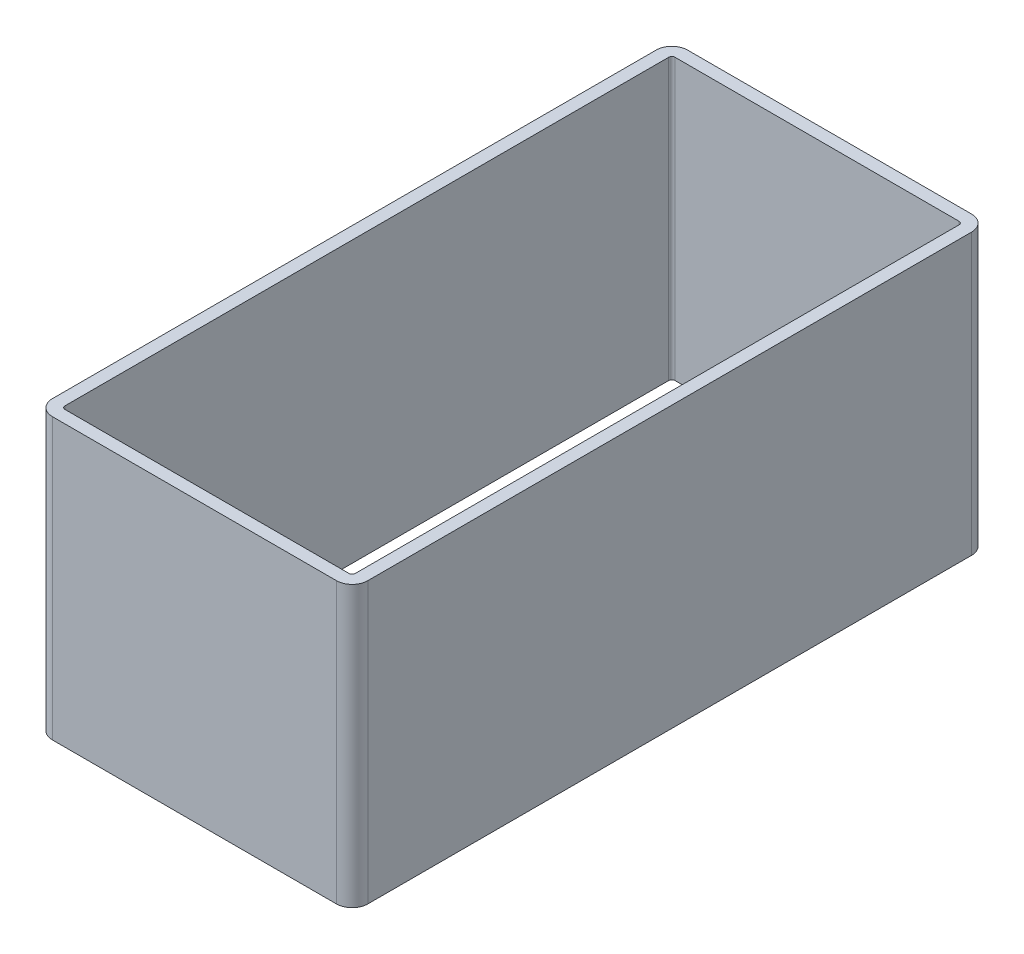
SolidWorks part; units mm, degrees
material "PC High Viscosity"
ref_plane "Front Plane" through (0, 0, 0) normal (0, 0, 1) x (1, 0, 0)
ref_plane "Top Plane" through (0, 0, 0) normal (0, 1, 0) x (1, 0, 0)
ref_plane "Right Plane" through (0, 0, 0) normal (1, 0, 0) x (0, 0, -1)
sketch "BaseS" plane through (0, 0, 0) normal (0, 1, 0) x (1, 0, 0)
  line L1 (-10.08, 20.3) -> (10.08, 20.3)
  line L2 (-10.08, 20.3) -> (-10.08, -20.3)
  line L3 (-10.08, -20.3) -> (10.08, -20.3)
  line L4 (10.08, 20.3) -> (10.08, -20.3)
  line L5 (-10.08, 20.3) -> (10.08, -20.3) construction
  line L6 (-10.08, -20.3) -> (10.08, 20.3) construction
  point P0 (0, 0)
  dimension "D1" = 20.16
  dimension "D2" = 40.6
extrude "BASE" add sketch "BaseS" along normal mid plane 17.9
fillet "BASE F" radius 1 4 edges at (-10.08, 0, -20.3) (10.08, 0, -20.3) (10.08, 0, 20.3) (-10.08, 0, 20.3)
sketch "PocketS" plane through (0, 8.95, 0) normal (0, 1, 0) x (1, 0, 0)
  line L0 (9.08, 19.5) -> (-9.08, 19.5)
  line L1 (-9.28, 19.3) -> (-9.28, -19.3)
  line L2 (-9.08, -19.5) -> (9.08, -19.5)
  line L3 (9.28, -19.3) -> (9.28, 19.3)
  line L4 (9.08, 20.3) -> (-9.08, 20.3)
  line L5 (-10.08, 19.3) -> (-10.08, -19.3)
  line L6 (-9.08, -20.3) -> (9.08, -20.3)
  line L7 (10.08, -19.3) -> (10.08, 19.3)
  line L8 (9.08, 20.3) -> (-9.08, 20.3) construction
  line L9 (-10.08, 19.3) -> (-10.08, -19.3) construction
  line L10 (-9.08, -20.3) -> (9.08, -20.3) construction
  line L11 (10.08, -19.3) -> (10.08, 19.3) construction
  arc A0 (-9.08, 19.5) -> (-9.28, 19.3) centre (-9.08, 19.3) ccw
  arc A1 (-9.28, -19.3) -> (-9.08, -19.5) centre (-9.08, -19.3) ccw
  arc A2 (9.08, -19.5) -> (9.28, -19.3) centre (9.08, -19.3) ccw
  arc A3 (9.28, 19.3) -> (9.08, 19.5) centre (9.08, 19.3) ccw
  arc A4 (-9.08, 20.3) -> (-10.08, 19.3) centre (-9.08, 19.3) ccw
  arc A5 (-10.08, -19.3) -> (-9.08, -20.3) centre (-9.08, -19.3) ccw
  arc A6 (9.08, -20.3) -> (10.08, -19.3) centre (9.08, -19.3) ccw
  arc A7 (10.08, 19.3) -> (9.08, 20.3) centre (9.08, 19.3) ccw
  arc A8 (-9.08, 20.3) -> (-10.08, 19.3) centre (-9.08, 19.3) ccw construction
  arc A9 (-10.08, -19.3) -> (-9.08, -20.3) centre (-9.08, -19.3) ccw construction
  arc A10 (9.08, -20.3) -> (10.08, -19.3) centre (9.08, -19.3) ccw construction
  arc A11 (10.08, 19.3) -> (9.08, 20.3) centre (9.08, 19.3) ccw construction
  dimension "D1" = 0
  dimension "D2" = 0.8
extrude "Cut-Extrude3" cut sketch "PocketS" against normal through all
